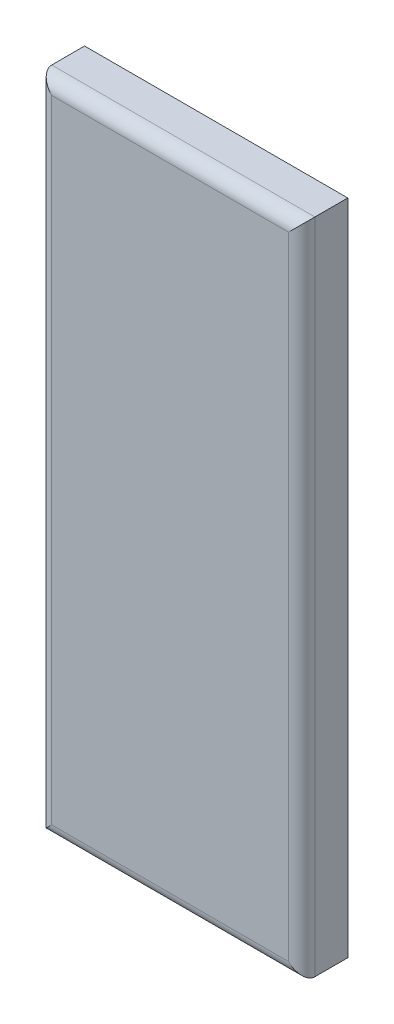
SolidWorks part; units mm, degrees
ref_plane "Front Plane" through (0, 0, 0) normal (0, 0, 1) x (1, 0, 0)
ref_plane "Top Plane" through (0, 0, 0) normal (0, 1, 0) x (1, 0, 0)
ref_plane "Right Plane" through (0, 0, 0) normal (1, 0, 0) x (0, 0, -1)
sketch "Sketch1" plane through (0, 0, 0) normal (0, 0, 1) x (1, 0, 0)
  line L1 (-20, 50) -> (20, 50)
  line L2 (-20, 50) -> (-20, -50)
  line L3 (-20, -50) -> (20, -50)
  line L4 (20, 50) -> (20, -50)
  line L5 (-20, 50) -> (20, -50) construction
  line L6 (-20, -50) -> (20, 50) construction
  point P0 (0, 0)
  dimension "D1" = 40
  dimension "D2" = 100
extrude "Boss-Extrude1" add sketch "Sketch1" along normal blind 7
fillet "Fillet1" radius 2 4 edges at (-20, 0, 7) (0, -50, 7) (20, 0, 7) (0, 50, 7)
